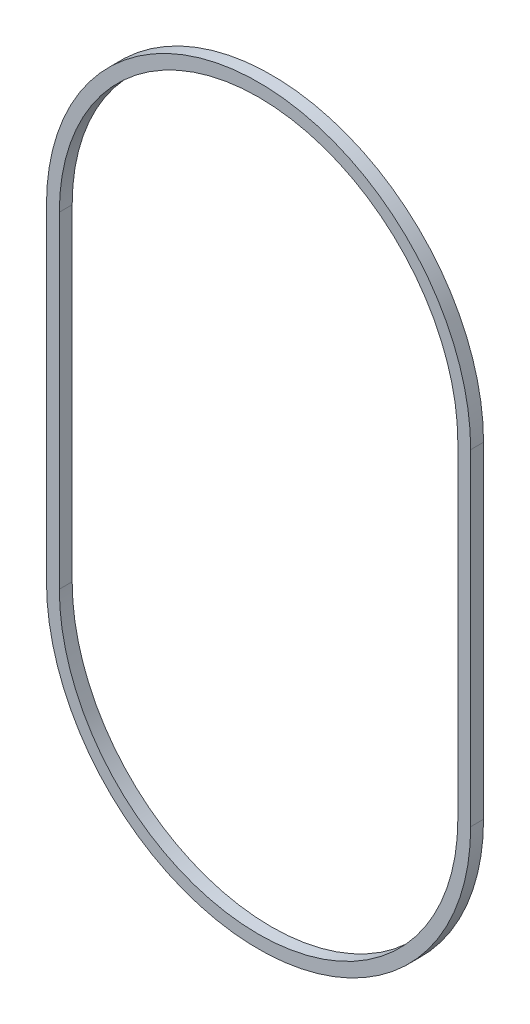
SolidWorks part; units mm, degrees
ref_plane "Front Plane" through (0, 0, 0) normal (0, 0, 1) x (1, 0, 0)
ref_plane "Top Plane" through (0, 0, 0) normal (0, 1, 0) x (1, 0, 0)
ref_plane "Right Plane" through (0, 0, 0) normal (1, 0, 0) x (0, 0, -1)
sketch "Sketch1" plane through (0, 0, 0) normal (0, 0, 1) x (1, 0, 0)
  line L0 (0, -31.75) -> (0, 31.75) construction
  line L1 (-38.75, -31.75) -> (-38.75, 31.75)
  line L2 (38.75, -31.75) -> (38.75, 31.75)
  line L3 (-41.25, -31.75) -> (-41.25, 31.75)
  line L4 (41.25, -31.75) -> (41.25, 31.75)
  arc A0 (-38.75, -31.75) -> (38.75, -31.75) centre (0, -31.75) ccw
  arc A1 (38.75, 31.75) -> (-38.75, 31.75) centre (0, 31.75) ccw
  arc A2 (41.25, 31.75) -> (-41.25, 31.75) centre (0, 31.75) ccw
  arc A3 (-41.25, -31.75) -> (41.25, -31.75) centre (0, -31.75) ccw
  point P2 (0, 0)
  dimension "D1" = 63.5
  dimension "D2" = 77.5
  dimension "D3" = 2.5
extrude "Boss-Extrude1" add sketch "Sketch1" along normal blind 2.5
